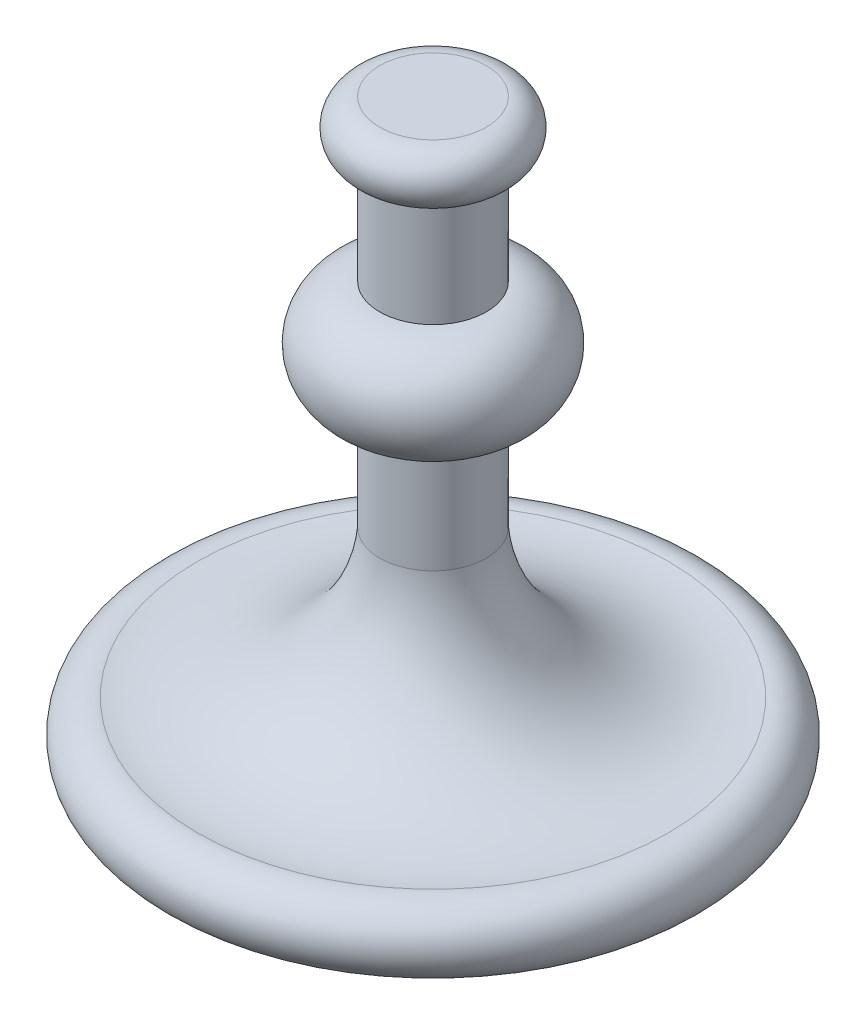
SolidWorks part; units mm, degrees
ref_plane "Płaszczyzna przednia" through (0, 0, 0) normal (0, 0, 1) x (1, 0, 0)
ref_plane "Płaszczyzna górna" through (0, 0, 0) normal (0, 1, 0) x (1, 0, 0)
ref_plane "Płaszczyzna prawa" through (0, 0, 0) normal (1, 0, 0) x (0, 0, -1)
sketch "Szkic1" plane through (0, 0, 0) normal (0, 0, 1) x (1, 0, 0)
  line L0 (0, 0) -> (0, 220)
  line L1 (0, 0) -> (90, 0)
  line L2 (0, 220) -> (20, 220)
  line L3 (20, 200) -> (20, 160)
  line L4 (20, 120) -> (20, 80)
  arc A0 (20, 220) -> (20, 200) centre (20, 210) cw
  arc A1 (20, 160) -> (20, 120) centre (20, 140) cw
  arc A2 (90, 0) -> (88.2494, 24.8768) centre (90, 12.5) ccw
  arc A3 (88.2494, 24.8768) -> (20, 80) centre (79.8468, 84.2855) cw
  dimension "D4" = 10
  dimension "D6" = 20
  dimension "D7" = 12.5
  dimension "D8" = 60
  dimension "D1" = 220
  dimension "D2" = 90
  dimension "D3" = 20
  dimension "D5" = 40
  dimension "D9" = 80
revolve "Obrót1" add sketch "Szkic1" angle 360 about L0
